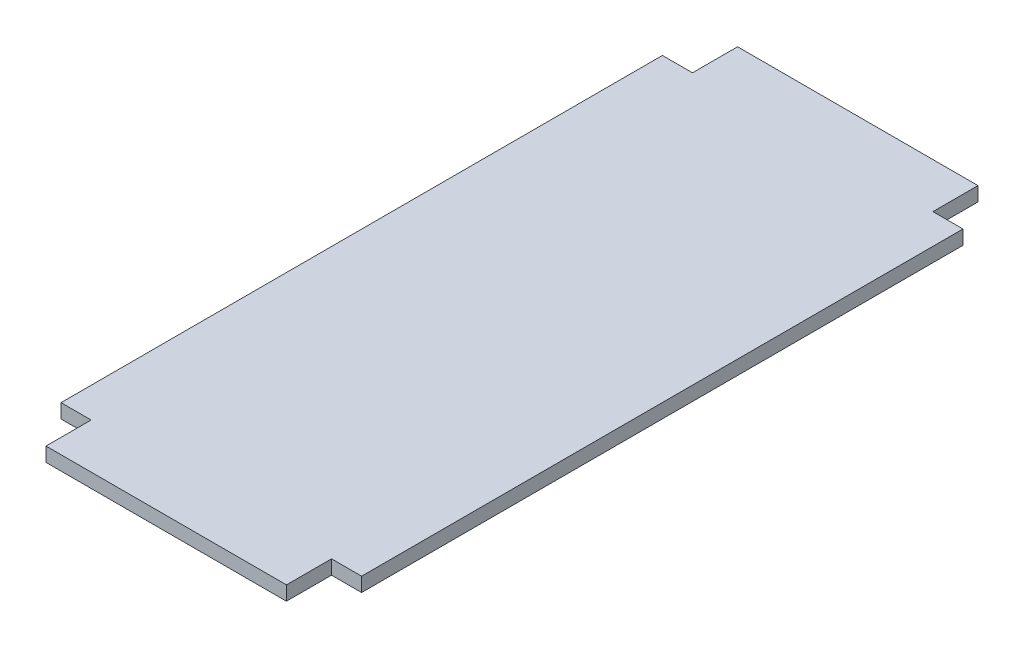
SolidWorks part; units mm, degrees
ref_plane "Front Plane" through (0, 0, 0) normal (0, 0, 1) x (1, 0, 0)
ref_plane "Top Plane" through (0, 0, 0) normal (0, 1, 0) x (1, 0, 0)
ref_plane "Right Plane" through (0, 0, 0) normal (1, 0, 0) x (0, 0, -1)
sketch "Sketch1" plane through (0, 0, 0) normal (0, 1, 0) x (1, 0, 0)
  line L0 (-31.7373, 66.4972) -> (31.7373, 66.4972) construction
  line L1 (31.7373, -73.025) -> (-31.7373, -73.025)
  line L2 (31.7373, -73.025) -> (31.7373, 73.025)
  line L3 (31.7373, 73.025) -> (-31.7373, 73.025)
  line L4 (-31.7373, -73.025) -> (-31.7373, 73.025)
  line L5 (31.7373, -73.025) -> (-31.7373, 73.025) construction
  line L6 (31.7373, 73.025) -> (-31.7373, -73.025) construction
  line L7 (-31.7373, -66.4972) -> (31.7373, -66.4972) construction
  line L8 (-31.7373, 66.4972) -> (-31.7373, -66.4972) construction
  line L9 (31.7373, 66.4972) -> (31.7373, -66.4972) construction
  line L20 (-31.7373, -73.025) -> (-25.3873, -73.025)
  line L29 (-31.7373, -73.025) -> (-31.7373, -63.5)
  line L30 (-31.7373, -63.5) -> (-25.3873, -63.5)
  line L31 (-25.3873, -73.025) -> (-25.3873, -63.5)
  line L32 (31.7373, -73.025) -> (25.3873, -73.025)
  line L33 (31.7373, -73.025) -> (31.7373, -63.5)
  line L34 (31.7373, -63.5) -> (25.3873, -63.5)
  line L35 (25.3873, -73.025) -> (25.3873, -63.5)
  line L36 (-31.7373, 73.025) -> (-25.3873, 73.025)
  line L37 (-31.7373, 73.025) -> (-31.7373, 63.5)
  line L38 (-31.7373, 63.5) -> (-25.3873, 63.5)
  line L39 (-25.3873, 73.025) -> (-25.3873, 63.5)
  line L40 (31.7373, 73.025) -> (25.3873, 73.025)
  line L41 (31.7373, 73.025) -> (31.7373, 63.5)
  line L42 (31.7373, 63.5) -> (25.3873, 63.5)
  line L43 (25.3873, 73.025) -> (25.3873, 63.5)
  point P0 (0, 0)
  point P10 (31.7373, 0)
  point P11 (31.7373, 0)
  dimension "D1" = 63.4746
  dimension "D2" = 146.05
  dimension "D3" = 132.9944
  dimension "D4" = 127
  dimension "D5" = 6.35
extrude "Boss-Extrude1" add sketch "Sketch1" along normal blind 2.9972
